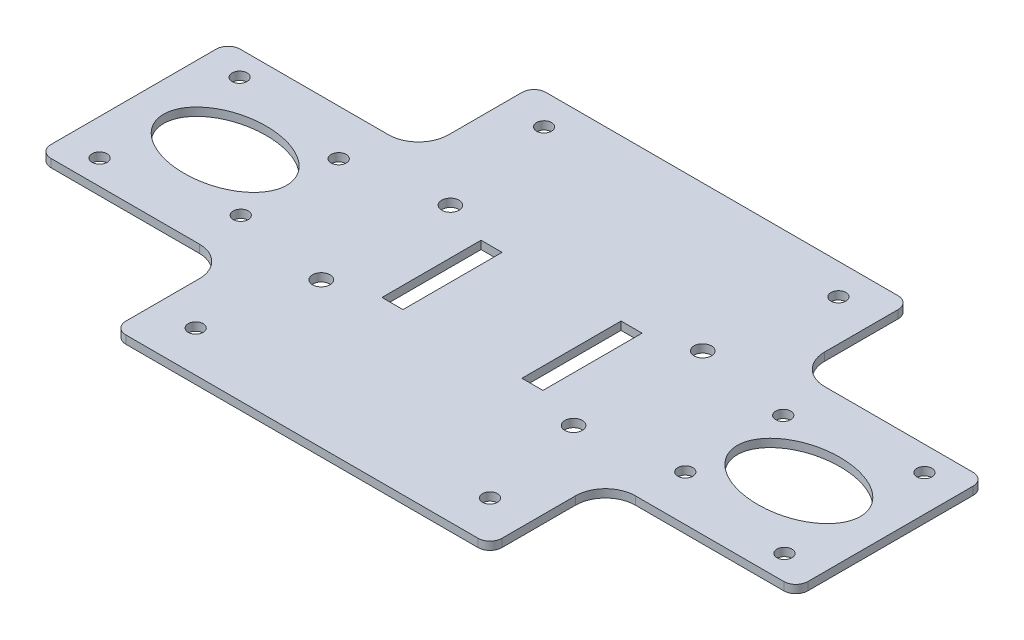
SolidWorks part; units mm, degrees
ref_plane "Front Plane" through (0, 0, 0) normal (0, 0, 1) x (1, 0, 0)
ref_plane "Top Plane" through (0, 0, 0) normal (0, 1, 0) x (1, 0, 0)
ref_plane "Right Plane" through (0, 0, 0) normal (1, 0, 0) x (0, 0, -1)
sketch "Sketch2" plane through (0, 0, 0) normal (0, 1, 0) x (1, 0, 0)
  line L0 (63, 0) -> (-63, 0) construction
  line L1 (25, -31.66) -> (-25, -31.66) construction
  line L2 (25, -31.66) -> (-25, -31.66) construction
  line L3 (28, 50.34) -> (28, -28.66) construction
  line L4 (28, 50.34) -> (28, -28.66) construction
  line L5 (-29.305, -34.965) -> (29.305, -34.965)
  line L6 (28, -28.66) -> (31.305, -28.66) construction
  line L7 (0, -31.66) -> (0, -34.965) construction
  line L8 (-29.305, 34.965) -> (29.305, 34.965)
  line L9 (31.305, 32.965) -> (31.305, 20.75)
  line L10 (-31.305, 20.75) -> (-31.305, 32.965)
  line L24 (63, -13.75) -> (63, 13.75)
  line L25 (61, 15.75) -> (36.305, 15.75)
  line L29 (-36.305, 15.75) -> (-61, 15.75)
  line L30 (-63, 13.75) -> (-63, -13.75)
  line L31 (-61, -15.75) -> (-36.305, -15.75)
  line L32 (-31.305, -20.75) -> (-31.305, -32.965)
  line L34 (31.305, -32.965) -> (31.305, -20.75)
  line L35 (36.305, -15.75) -> (61, -15.75)
  arc A0 (-31.305, -32.965) -> (-29.305, -34.965) centre (-29.305, -32.965) ccw
  arc A1 (29.305, -34.965) -> (31.305, -32.965) centre (29.305, -32.965) ccw
  circle A2 centre (21, -10.75) radius 1.45
  arc A3 (-31.305, 32.965) -> (-29.305, 34.965) centre (-29.305, 32.965) cw
  circle A4 centre (21, 10.75) radius 1.45
  arc A5 (29.305, 34.965) -> (31.305, 32.965) centre (29.305, 32.965) cw
  circle A6 centre (-21, 10.75) radius 1.45
  circle A7 centre (-24.5, 29.84) radius 1.25
  circle A8 centre (-21, -10.75) radius 1.45
  circle A9 centre (-24.5, -28.16) radius 1.25
  circle A10 centre (-57, -11.65) radius 1.25
  circle A11 centre (24.5, -28.16) radius 1.25
  circle A12 centre (-57, 11.65) radius 1.25
  circle A13 centre (24.5, 29.84) radius 1.25
  circle A14 centre (57, 11.65) radius 1.25
  circle A16 centre (-37, 8.15) radius 1.25
  circle A18 centre (-37, -8.15) radius 1.25
  circle A20 centre (37, -8.15) radius 1.25
  circle A22 centre (37, 8.15) radius 1.25
  circle A24 centre (57, -11.65) radius 1.25
  arc A48 (63, 13.75) -> (61, 15.75) centre (61, 13.75) ccw
  arc A49 (31.305, 20.75) -> (36.305, 15.75) centre (36.305, 20.75) ccw
  arc A52 (-36.305, 15.75) -> (-31.305, 20.75) centre (-36.305, 20.75) ccw
  arc A53 (-61, 15.75) -> (-63, 13.75) centre (-61, 13.75) ccw
  arc A54 (-63, -13.75) -> (-61, -15.75) centre (-61, -13.75) ccw
  arc A55 (-31.305, -20.75) -> (-36.305, -15.75) centre (-36.305, -20.75) ccw
  arc A58 (36.305, -15.75) -> (31.305, -20.75) centre (36.305, -20.75) ccw
  arc A59 (61, -15.75) -> (63, -13.75) centre (61, -13.75) ccw
  point P68 (24.5, -28.16)
  point P69 (-24.5, -28.16)
  point P71 (-24.5, 29.84)
  point P73 (24.5, 29.84)
  dimension "D1" = 2.5
extrude "Boss-Extrude1" add sketch "Sketch2" against normal blind 1.35
sketch "Sketch5" plane through (0, 0, 0) normal (0, 1, 0) x (1, 0, 0)
  line L4 (13.4, 8.25) -> (9.9, 8.25)
  line L5 (9.9, 8.25) -> (9.9, -8.25)
  line L6 (9.9, -8.25) -> (13.4, -8.25)
  line L7 (13.4, -8.25) -> (13.4, 8.25)
  line L8 (13.4, 8.25) -> (9.9, 8.25)
  line L9 (9.9, 8.25) -> (9.9, -8.25)
  line L10 (9.9, -8.25) -> (13.4, -8.25)
  line L11 (13.4, -8.25) -> (13.4, 8.25)
  line L12 (-9.9, 8.25) -> (-13.4, 8.25)
  line L13 (-13.4, 8.25) -> (-13.4, -8.25)
  line L14 (-13.4, -8.25) -> (-9.9, -8.25)
  line L15 (-9.9, -8.25) -> (-9.9, 8.25)
  line L16 (-9.9, 8.25) -> (-13.4, 8.25)
  line L17 (-13.4, 8.25) -> (-13.4, -8.25)
  line L18 (-13.4, -8.25) -> (-9.9, -8.25)
  line L19 (-9.9, -8.25) -> (-9.9, 8.25)
  ellipse E0 centre (47.75, 0) end of major axis (37.5, 0) minor radius 6.825 construction
  ellipse E1 centre (47.75, 0) end of major axis (37.5, 0) minor radius 6.825
  ellipse E2 centre (-47.75, 0) end of major axis (-37.5, 0) minor radius 6.825 construction
  ellipse E3 centre (-47.75, 0) end of major axis (-37.5, 0) minor radius 6.825
  dimension "D5" = 0
  dimension "D7" = 0
extrude "Cut-Extrude1" cut sketch "Sketch5" against normal up to next
equation "\"Black_acrylic\"= 1.35mm"
equation "\"MDF_base\"= 20mm"
equation "\"Supports_material\"= 5.4mm"
